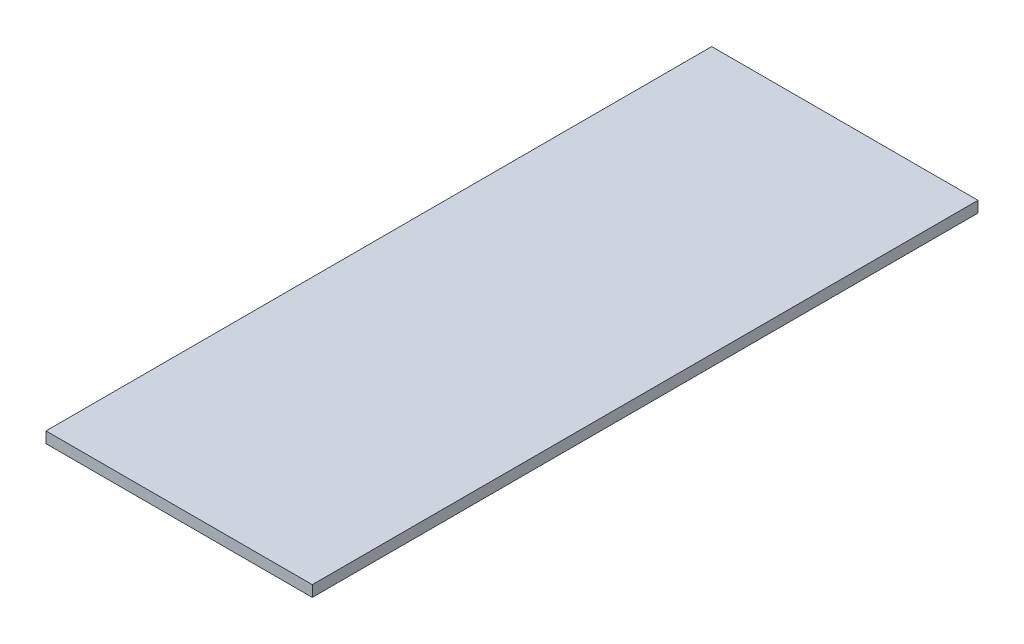
SolidWorks part; units mm, degrees
material "Acrylic (Medium-high impact)"
ref_plane "Front Plane" through (0, 0, 0) normal (0, 0, 1) x (1, 0, 0)
ref_plane "Top Plane" through (0, 0, 0) normal (0, 1, 0) x (1, 0, 0)
ref_plane "Right Plane" through (0, 0, 0) normal (1, 0, 0) x (0, 0, -1)
sketch "Sketch1" plane through (0, 0, 0) normal (0, 1, 0) x (1, 0, 0)
  line L1 (-101.4026, 303.7813) -> (50.9974, 303.7813)
  line L2 (-101.4026, 303.7813) -> (-101.4026, -77.2187)
  line L3 (-101.4026, -77.2187) -> (50.9974, -77.2187)
  line L4 (50.9974, 303.7813) -> (50.9974, -77.2187)
  dimension "D1" = 381
  dimension "D2" = 152.4
extrude "Extrude1" add sketch "Sketch1" along normal blind 6.35
